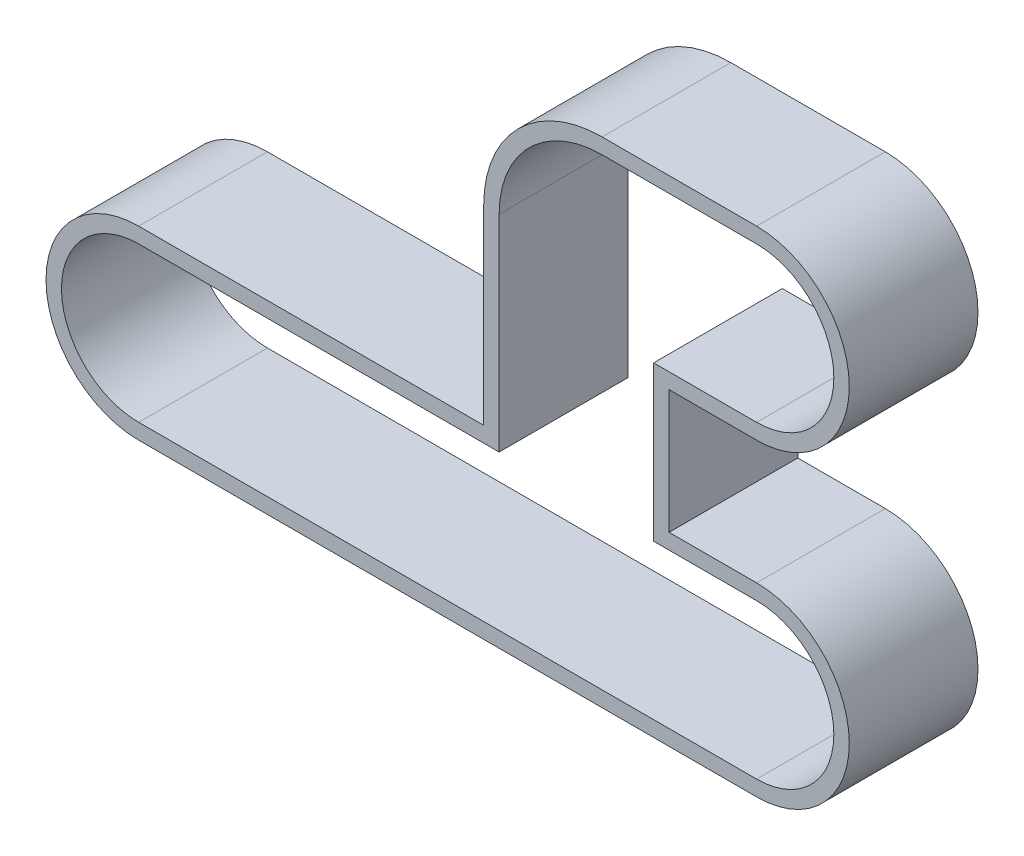
SolidWorks part; units mm, degrees
ref_plane "Front Plane" through (0, 0, 0) normal (0, 0, 1) x (1, 0, 0)
ref_plane "Top Plane" through (0, 0, 0) normal (0, 1, 0) x (1, 0, 0)
ref_plane "Right Plane" through (0, 0, 0) normal (1, 0, 0) x (0, 0, -1)
sketch "Sketch2" plane through (0, 0, 0) normal (0, 0, 1) x (1, 0, 0)
  line L0 (0, 0) -> (120, 0)
  line L1 (120, 30) -> (100, 30)
  line L2 (100, 30) -> (100, 60)
  line L3 (100, 60) -> (120, 60)
  line L4 (120, 90) -> (90, 90)
  line L5 (70, 70) -> (70, 30)
  line L6 (70, 30) -> (0, 30)
  arc A0 (120, 0) -> (120, 30) centre (120, 15) ccw
  arc A1 (120, 60) -> (120, 90) centre (120, 75) ccw
  arc A2 (0, 30) -> (0, 0) centre (0, 15) ccw
  arc A3 (90, 90) -> (70, 70) centre (90, 70) ccw
  point P14 (0, 0)
  point P17 (70, 90)
  dimension "D2" = 15
  dimension "D3" = 15
  dimension "D9" = 20
  dimension "D1" = 120
  dimension "D4" = 30
  dimension "D5" = 30
  dimension "D6" = 70
  dimension "D7" = 50
  dimension "D8" = 60
extrude "Extrude-Thin11" add sketch "Sketch2" along normal blind 25 thin
